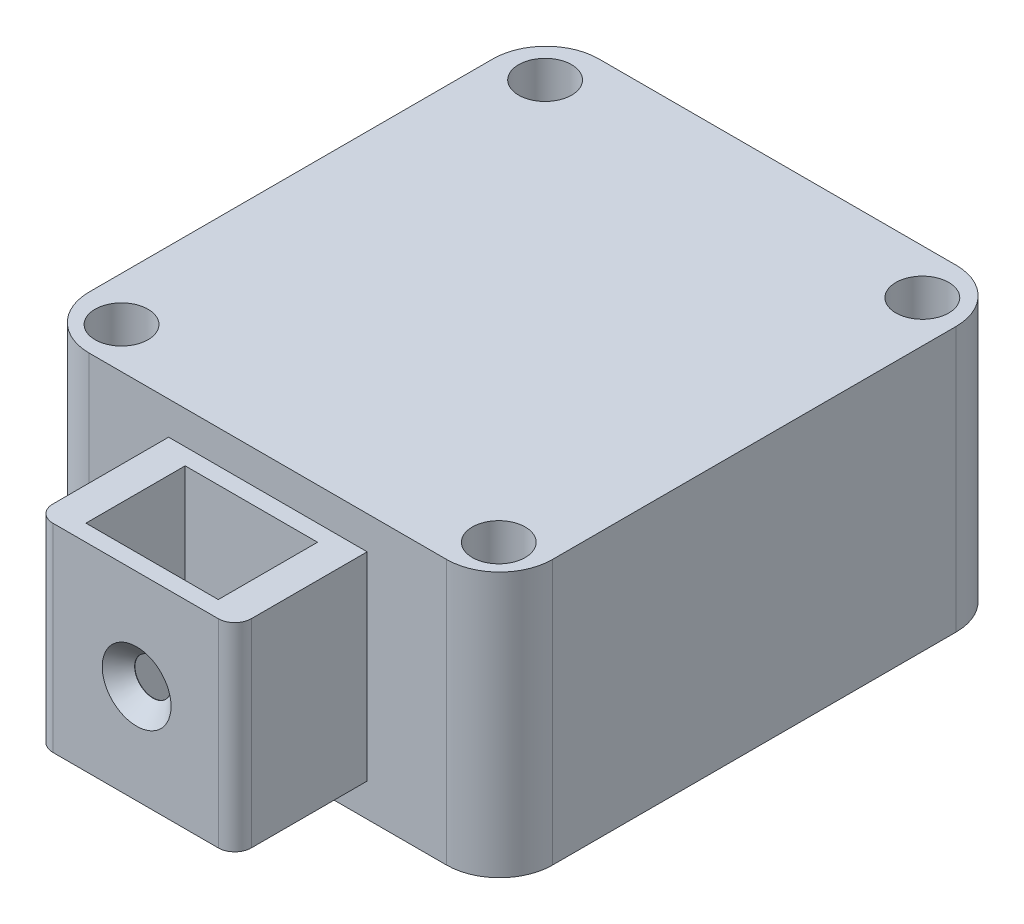
SolidWorks part; units mm, degrees
ref_plane "Front Plane" through (0, 0, 0) normal (0, 0, 1) x (1, 0, 0)
ref_plane "Top Plane" through (0, 0, 0) normal (0, 1, 0) x (1, 0, 0)
ref_plane "Right Plane" through (0, 0, 0) normal (1, 0, 0) x (0, 0, -1)
sketch "Sketch4" plane through (0, 0, 0) normal (0, 1, 0) x (1, 0, 0)
  line L1 (-35.1934, 38.8094) -> (34.8066, 38.8094)
  line L2 (-35.1934, 38.8094) -> (-35.1934, -38.1906)
  line L3 (-35.1934, -38.1906) -> (34.8066, -38.1906)
  line L4 (34.8066, 38.8094) -> (34.8066, -38.1906)
  line L5 (-35.1934, 38.8094) -> (34.8066, -38.1906) construction
  line L6 (-35.1934, -38.1906) -> (34.8066, 38.8094) construction
  point P0 (-0.1934, 0.3094)
  dimension "D1" = 70
  dimension "D2" = 77
extrude "Boss-Extrude1" add sketch "Sketch4" along normal blind 40
sketch "Sketch5" plane through (0, 40, 0) normal (0, 1, 0) x (1, 0, 0)
  line L0 (-24.5, 32) -> (24.5, 32)
  line L1 (-28.5, 28) -> (-28.5, -28)
  line L2 (-24.5, -32) -> (24.5, -32)
  line L3 (28.5, 28) -> (28.5, -28)
  line L4 (-28.5, 32) -> (25.8396, -29.0129) construction
  line L5 (-25.8396, -29.0129) -> (28.5, 32) construction
  circle A0 centre (-28.5, 32) radius 4
  circle A1 centre (28.5, 32) radius 4
  circle A2 centre (-28.5, -32) radius 4
  circle A3 centre (28.5, -32) radius 4
  point P0 (0, 0)
  line M1 (34.8066, -38.1906) -> (34.8066, 38.8094)
  dimension "D2" = 8
extrude "Cut-Extrude1" cut sketch "Sketch5" against normal blind 30 contours A2 | A3 | A1 | A0 M1
sketch "Sketch6" plane through (0, 0, 38.1906) normal (0, 0, 1) x (1, 0, 0)
  line L0 (-35.1934, 0) -> (34.8066, 0) construction
  line L1 (-15.1934, 35) -> (14.8066, 35)
  line L2 (-15.1934, 35) -> (-15.1934, 5)
  line L3 (-15.1934, 5) -> (14.8066, 5)
  line L4 (14.8066, 35) -> (14.8066, 5)
  line L5 (-35.1934, 40) -> (-35.1934, 0) construction
  dimension "D1" = 30
  dimension "D2" = 5
  dimension "30" = 30
  dimension "D3" = 20
extrude "Boss-Extrude3" add sketch "Sketch6" along normal blind 20
sketch "Sketch7" plane through (0, 35, 0) normal (0, 1, 0) x (1, 0, 0)
  line L1 (-10.1934, -40.6906) -> (9.8066, -40.6906)
  line L2 (-10.1934, -40.6906) -> (-10.1934, -55.6906)
  line L3 (-10.1934, -55.6906) -> (9.8066, -55.6906)
  line L4 (9.8066, -40.6906) -> (9.8066, -55.6906)
  line L5 (14.8066, -38.1906) -> (-15.1934, -38.1906) construction
  line L6 (14.8066, -58.1906) -> (14.8066, -38.1906) construction
  dimension "D1" = 20
  dimension "D2" = 15
  dimension "D3" = 5
  dimension "D4" = 2.5
extrude "Cut-Extrude2" cut sketch "Sketch7" against normal blind 30
sketch "Sketch8" plane through (0, 0, 58.1906) normal (0, 0, 1) x (1, 0, 0)
  line L0 (-10.1524, 29.9179) -> (9.9303, 9.9175) construction
  line L1 (9.9303, 9.9175) -> (9.7657, 29.9179) construction
  line L2 (9.7657, 29.9179) -> (-9.9878, 9.9175) construction
hole_wizard "CSK for M5 Countersunk Flat Head Screw1" positions "Sketch9" profile "Sketch10" countersink size "M5" standard "DIN"
sketch "Sketch9" plane through (0, 0, 58.1906) normal (0, 0, 1) x (1, 0, 0)
  point P0 (-0.0288, 19.9588)
sketch "Sketch10" plane through (-0.0288, 19.9588, 58.1906) normal (1, 0, 0) x (0, -1, 0)
  line L0 (0, 0) -> (0, 31.6524)
  line L1 (0, 31.6524) -> (2.75, 30)
  line L2 (2.75, 30) -> (2.75, 2.45)
  line L3 (2.75, 2.45) -> (5.2, 0)
  line L5 (5.2, 0) -> (0, 0)
  line L6 (-2.75, 2.45) -> (-5.2, 0) construction
  line L10 (0, 31.6524) -> (-2.75, 30) construction
  line L11 (0, -6.35) -> (0, 107.95) construction
  dimension "Hole Dia." = 5.5
  dimension "Hole Depth" = 30
  dimension "Near C'Sink Dia." = 10.4
  dimension "Near C'Sink Angle" = 90
  dimension "Drill Angle" = 118
fillet "Fillet1" radius 8 4 edges at (34.8066, 20, 38.1906) (34.8066, 20, -38.8094) (-35.1934, 20, -38.8094) (-35.1934, 20, 38.1906)
fillet "Fillet2" radius 2.5 2 edges at (14.8066, 20, 58.1906) (-15.1934, 20, 58.1906)
